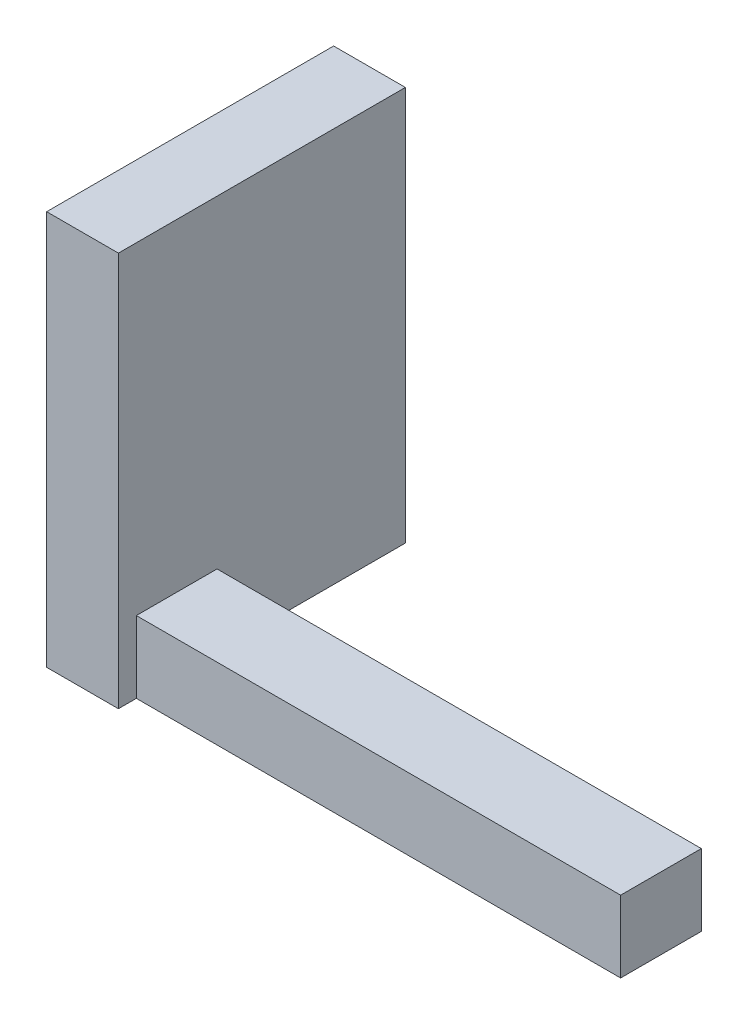
SolidWorks part; units mm, degrees
ref_plane "Front Plane" through (0, 0, 0) normal (0, 0, 1) x (1, 0, 0)
ref_plane "Top Plane" through (0, 0, 0) normal (0, 1, 0) x (1, 0, 0)
ref_plane "Right Plane" through (0, 0, 0) normal (1, 0, 0) x (0, 0, -1)
other "Configuration Table"
sketch "Sketch1" plane through (0, 0, 0) normal (1, 0, 0) x (0, 0, -1)
  line L1 (-24, 66) -> (-40, 66)
  line L2 (-24, 66) -> (-24, 88)
  line L3 (-24, 88) -> (-40, 88)
  line L4 (-40, 66) -> (-40, 88)
  line L5 (-24, 66) -> (-40, 88) construction
  line L6 (-24, 88) -> (-40, 66) construction
  point P0 (-32, 77)
extrude "column" add sketch "Sketch1" along normal blind 4 from offset 46 separate body
sketch "Sketch2" plane through (0, 0, 0) normal (1, 0, 0) x (0, 0, -1)
  line L1 (-34.5, 66) -> (-39, 66)
  line L2 (-34.5, 66) -> (-34.5, 70)
  line L3 (-34.5, 70) -> (-39, 70)
  line L4 (-39, 66) -> (-39, 70)
  line L5 (-34.5, 66) -> (-39, 70) construction
  line L6 (-34.5, 70) -> (-39, 66) construction
  point P0 (-36.75, 68)
extrude "anchor_plate" add sketch "Sketch2" along normal blind 31 from offset 46 separate body
